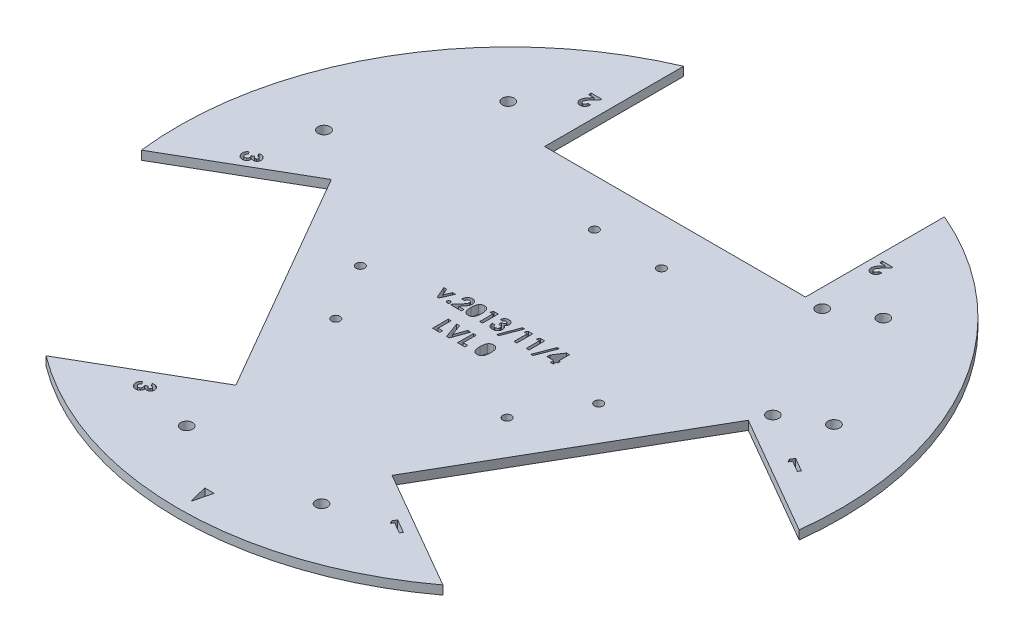
SolidWorks part; units mm, degrees
ref_plane "Front" through (0, 0, 0) normal (0, 0, 1) x (1, 0, 0)
ref_plane "Top" through (0, 0, 0) normal (0, 1, 0) x (1, 0, 0)
ref_plane "Right" through (0, 0, 0) normal (1, 0, 0) x (0, 0, -1)
sketch "Sketch1" plane through (0, 0, 0) normal (0, 1, 0) x (1, 0, 0)
  line L0 (-35, 44.4119) -> (-35, 81.7203)
  line L1 (-35, 44.4119) -> (35, 44.4119)
  line L2 (35, 44.4119) -> (35, 81.7203)
  line L3 (55.9618, 8.1049) -> (88.2719, -10.5493)
  line L4 (55.9618, 8.1049) -> (20.9618, -52.5168)
  line L5 (20.9618, -52.5168) -> (53.2719, -71.171)
  line L6 (0, 0) -> (0, 50000) construction
  line L7 (0, 0) -> (50000, 0) construction
  line L8 (0, 0) -> (38.4618, -22.206) construction
  line L9 (0, 0) -> (-38.4618, -22.206) construction
  line L12 (-20.9618, -52.5168) -> (-53.2719, -71.171)
  line L15 (-20.9618, -52.5168) -> (-55.9618, 8.1049)
  line L16 (-55.9618, 8.1049) -> (-88.2719, -10.5493)
  arc A0 (-35, 81.7203) -> (-88.2719, -10.5493) centre (0, 0) ccw
  arc A1 (88.2719, -10.5493) -> (35, 81.7203) centre (0, 0) ccw
  arc A2 (-53.2719, -71.171) -> (53.2719, -71.171) centre (0, 0) ccw
  point P28 (0, 0)
  point P57 (0, 0)
  dimension "D1" = 3
  dimension "D2" = 70
  dimension "D3" = 37.3084
  dimension "D12" = 88.9
  dimension "D5" = 44.4119
  dimension "D6" = 52.5168
  dimension "D11" = 20.9618
  dimension "D14" = 120
  dimension "D15" = 120
extrude "Acrilic, Wheels and Motor mounting holes" add sketch "Sketch1" along normal blind 2.3622
sketch "Sketch3" plane through (0, 2.3622, 0) normal (0, 1, 0) x (1, 0, 0)
  line L0 (0, 0) -> (0, -50000) construction
  line L1 (0, 0) -> (50000, 0) construction
  line L3 (-35, 63.0661) -> (-44.5294, 63.0661) construction
  line L4 (-35, 44.4119) -> (-35, 81.7203) construction
  line L5 (35, 63.0661) -> (44.5294, 63.0661) construction
  line L6 (72.1169, -1.2222) -> (76.8816, 7.0305) construction
  line L7 (37.1169, -61.8439) -> (32.3522, -70.0966) construction
  line L8 (-37.1169, -61.8439) -> (-32.3522, -70.0966) construction
  line L9 (-72.1169, -1.2222) -> (-76.8816, 7.0305) construction
  line L10 (-1.25, -80.58) -> (0, -85.58)
  line L11 (0, -85.58) -> (1.25, -80.58)
  line L12 (1.25, -80.58) -> (-1.25, -80.58)
  line L13 (35, 81.7203) -> (35, 44.4119) construction
  line L18 (17.3205, -5) -> (-22.6795, -5) construction
  text T0 "<b>  2</b>"
  text T1 "<b>2 </b>"
  text T2 "<b>1 </b>"
  text T3 "<b>  1 </b>"
  text T4 "<b>  3</b>"
  text T5 "<b>3 </b>"
  text T6 "<b>v.2013/11/4</b>\r\n<b>LVL 0       </b>"
  point P20 (0, 0)
  point P38 (0, 0)
  dimension "D17" = 90
  dimension "D9" = 2.5
  dimension "D10" = 5
  dimension "D11" = 80.58
  dimension "D15" = 152.8914
  dimension "D16" = 5
  dimension "D18" = 40
  dimension "D8" = 3
extrude "Structure Mounting Holes" cut sketch "Sketch3" against normal up to surface (2.3622 mm away) up to face at (0, 0, 0)
delete or keep bodies "Body-Delete2" type delete bodies bodies 112 114 113
sketch "Sketch4" plane through (0, 2.3622, 0) normal (0, 1, 0) x (1, 0, 0)
  line L0 (0, 0) -> (50000, 0) construction
  line L1 (0, 0) -> (0, 50000) construction
  line L2 (-18.1, -68.58) -> (18.1, -68.58) construction
  line L3 (35, 81.7203) -> (35, 44.4119) construction
  line L4 (-9, 31.75) -> (9, 31.75) construction
  line L5 (35, 44.4119) -> (-35, 44.4119) construction
  circle A0 centre (-9, 31.75) radius 1.15
  circle A1 centre (9, 31.75) radius 1.15
  circle A2 centre (58.0497, 12.6149) radius 1.59
  circle A3 centre (39.9497, 43.9651) radius 1.59
  circle A4 centre (-18.1, -68.58) radius 1.59
  circle A5 centre (18.1, -68.58) radius 1.59
  circle A6 centre (22.9963, -23.6692) radius 1.15
  circle A7 centre (31.9963, -8.0808) radius 1.15
  circle A8 centre (-31.9963, -8.0808) radius 1.15
  circle A9 centre (-22.9963, -23.6692) radius 1.15
  circle A10 centre (-50.342, 49.9651) radius 1.59
  circle A11 centre (-68.442, 18.6149) radius 1.59
  circle A12 centre (68.442, 18.6149) radius 1.59
  circle A13 centre (50.342, 49.9651) radius 1.59
  point P30 (0, 0)
  point P39 (0, 0)
  dimension "D1" = 68.58
  dimension "D2" = 3.18
  dimension "D6" = 2.3
  dimension "D7" = 9
  dimension "D8" = 3
  dimension "D9" = 18.1
  dimension "D10" = 3
  dimension "D11" = 12
  dimension "D12" = 12
  dimension "D13" = 4.9497
  dimension "D15" = 23.0497
  dimension "D3" = 36.2
  dimension "D4" = 18
  dimension "D5" = 12.6619
  dimension "D14" = 15.342
extrude "Cut-Extrude1" cut sketch "Sketch4" against normal blind 10
